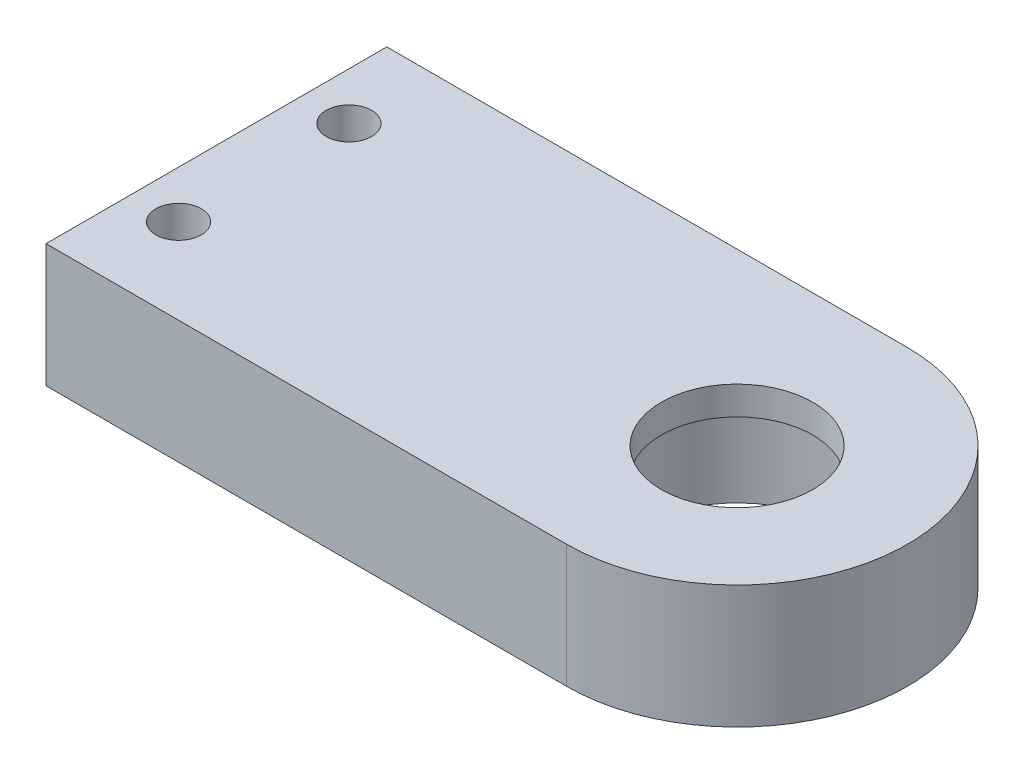
SolidWorks part; units mm, degrees
material "ABS"
ref_plane "Front Plane" through (0, 0, 0) normal (0, 0, 1) x (1, 0, 0)
ref_plane "Top Plane" through (0, 0, 0) normal (0, 1, 0) x (1, 0, 0)
ref_plane "Right Plane" through (0, 0, 0) normal (1, 0, 0) x (0, 0, -1)
ref_plane "Y+24_80" through (0, 24.8, 0) normal (0, 1, 0) x (1, 0, 0)
sketch "Sketch1" plane through (0, 24.8, 0) normal (0, 1, 0) x (1, 0, 0)
  line L0 (5.5, 9) -> (-22, 9)
  line L1 (-22, 9) -> (-22, -9)
  line L2 (-22, -9) -> (5.5, -9)
  arc A0 (5.5, -9) -> (5.5, 9) centre (5.5, 0) ccw
extrude "Boss-Extrude1" add sketch "Sketch1" along normal blind 6.5
sketch "Sketch2" plane through (0, 24.8, 0) normal (0, 1, 0) x (1, 0, 0)
  circle A0 centre (5.5, 0) radius 5.5
extrude "Cut-Extrude2" cut sketch "Sketch2" along normal blind 5
ref_plane "Y+29_80" through (0, 29.8, 0) normal (0, 1, 0) x (1, 0, 0)
sketch "Sketch3" plane through (0, 29.8, 0) normal (0, 1, 0) x (1, 0, 0)
  circle A0 centre (5.5, 0) radius 4
extrude "Cut-Extrude4" cut sketch "Sketch3" along normal blind 1.5
hole_wizard "M2 Clearance Hole1" positions "Sketch5" profile "Sketch4" hole size "M2" standard "ISO"
sketch "Sketch5" plane through (0, 31.3, 0) normal (0, 1, 0) x (1, 0, 0)
  point P0 (-19.5, -4.5)
sketch "Sketch4" plane through (-19.5, 31.3, 4.5) normal (1, 0, 0) x (0, 0, 1)
  line L0 (0, 0) -> (0, 6.5)
  line L1 (0, 6.5) -> (1.2, 6.5)
  line L2 (1.2, 6.5) -> (1.2, 0)
  line L5 (1.2, 0) -> (0, 0)
  line L11 (0, -6.35) -> (0, 107.95) construction
  dimension "Thru Hole Dia." = 2.4
  dimension "Thru Hole Depth" = 6.5
hole_wizard "M2 Clearance Hole2" positions "Sketch7" profile "Sketch6" hole size "M2" standard "ISO"
sketch "Sketch7" plane through (0, 31.3, 0) normal (0, 1, 0) x (1, 0, 0)
  point P0 (-19.5, 4.5)
sketch "Sketch6" plane through (-19.5, 31.3, -4.5) normal (1, 0, 0) x (0, 0, 1)
  line L0 (0, 0) -> (0, 6.5)
  line L1 (0, 6.5) -> (1.2, 6.5)
  line L2 (1.2, 6.5) -> (1.2, 0)
  line L5 (1.2, 0) -> (0, 0)
  line L11 (0, -6.35) -> (0, 107.95) construction
  dimension "Thru Hole Dia." = 2.4
  dimension "Thru Hole Depth" = 6.5
